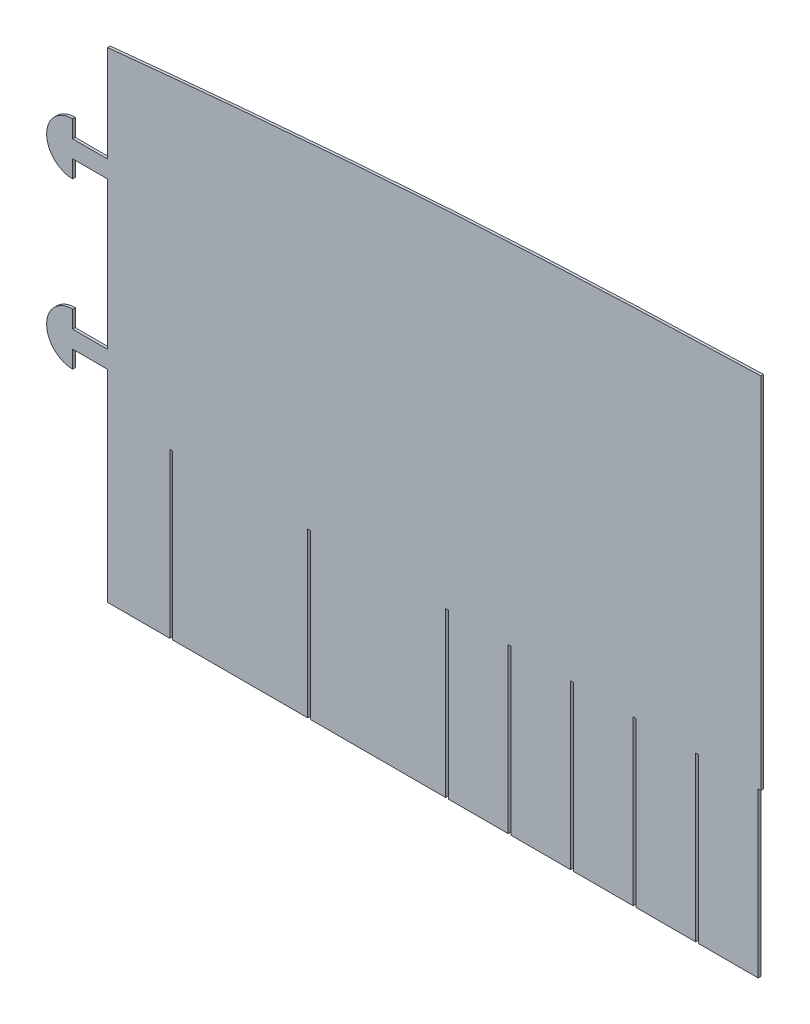
SolidWorks part; units mm, degrees
ref_plane "Front Plane" through (0, 0, 0) normal (0, 0, 1) x (1, 0, 0)
ref_plane "Top Plane" through (0, 0, 0) normal (0, 1, 0) x (1, 0, 0)
ref_plane "Right Plane" through (0, 0, 0) normal (1, 0, 0) x (0, 0, -1)
sketch "Model" plane through (0, 0, 0) normal (0, 0, 1) x (1, 0, 0)
  line L0 (1254.901, 442.6278) -> (1254.901, 462.6278)
  line L1 (1254.901, 402.6278) -> (1254.901, 422.6278)
  line L2 (1254.901, 422.6278) -> (1295.101, 422.6278)
  line L3 (1295.101, 252.6278) -> (1295.101, 422.6278)
  line L4 (1295.101, 252.6278) -> (1254.901, 252.6278)
  line L5 (1254.901, 252.6278) -> (1254.901, 272.6278)
  line L6 (1254.901, 212.6278) -> (1254.901, 232.6278)
  line L7 (1254.901, 232.6278) -> (1295.101, 232.6278)
  line L8 (1295.101, 0) -> (1295.101, 232.6278)
  line L9 (1295.101, 0) -> (1366.901, 0)
  line L10 (1366.901, 188.6103) -> (1366.901, 0)
  line L11 (1369.901, 188.6103) -> (1366.901, 188.6103)
  line L12 (1369.901, 0) -> (1369.901, 188.6103)
  line L13 (1369.901, 0) -> (1525.901, 0)
  line L14 (1525.901, 188.6103) -> (1525.901, 0)
  line L15 (1528.901, 188.6103) -> (1525.901, 188.6103)
  line L16 (1528.901, 0) -> (1528.901, 188.6103)
  line L17 (1528.901, 0) -> (1684.901, 0)
  line L18 (1684.901, 188.6103) -> (1684.901, 0)
  line L19 (1687.901, 188.6103) -> (1684.901, 188.6103)
  line L20 (1687.901, 0) -> (1687.901, 188.6103)
  line L21 (1687.901, 0) -> (1756.9435, 0)
  line L22 (1756.9435, 188.6103) -> (1756.9435, 0)
  line L23 (1759.9435, 188.6103) -> (1756.9435, 188.6103)
  line L24 (1759.9435, 0) -> (1759.9435, 188.6103)
  line L25 (1759.9435, 0) -> (1828.986, 0)
  line L26 (1828.986, 188.6103) -> (1828.986, 0)
  line L27 (1831.986, 188.6103) -> (1828.986, 188.6103)
  line L28 (1831.986, 0) -> (1831.986, 188.6103)
  line L29 (1831.986, 0) -> (1901.0286, 0)
  line L30 (1901.0286, 188.6103) -> (1901.0286, 0)
  line L31 (1904.0286, 188.6103) -> (1901.0286, 188.6103)
  line L32 (1904.0286, 0) -> (1904.0286, 188.6103)
  line L33 (1904.0286, 0) -> (1973.0711, 0)
  line L34 (1973.0711, 188.6103) -> (1973.0711, 0)
  line L35 (1976.0711, 188.6103) -> (1973.0711, 188.6103)
  line L36 (1976.0711, 0) -> (1976.0711, 188.6103)
  line L37 (1976.0711, 0) -> (2045.1136, 0)
  line L38 (2045.1136, 188.6103) -> (2045.1136, 0)
  line L39 (2048.1136, 188.6103) -> (2045.1136, 188.6103)
  line L40 (2048.1136, 188.6103) -> (2048.1136, 602.6278)
  line L41 (1295.101, 442.6278) -> (1295.101, 553.8894)
  line L42 (1254.901, 442.6278) -> (1295.101, 442.6278)
  arc A0 (1254.901, 462.6278) -> (1254.901, 402.6278) centre (1254.901, 432.6278) ccw
  arc A1 (1254.901, 272.6278) -> (1254.901, 212.6278) centre (1254.901, 242.6278) ccw
  spline S0 degree 3 poles (2048.1136, 602.6278) (1934.5964, 599.1114) (1718.6049, 592.1824) (1441.4869, 568.5414) (1295.101, 553.8894) knots 0.033635 0.033635 0.033635 0.033635 0.070138 0.108742 0.108742 0.108742 0.108742
extrude "Boss-Extrude1" add sketch "Model" along normal blind 3
